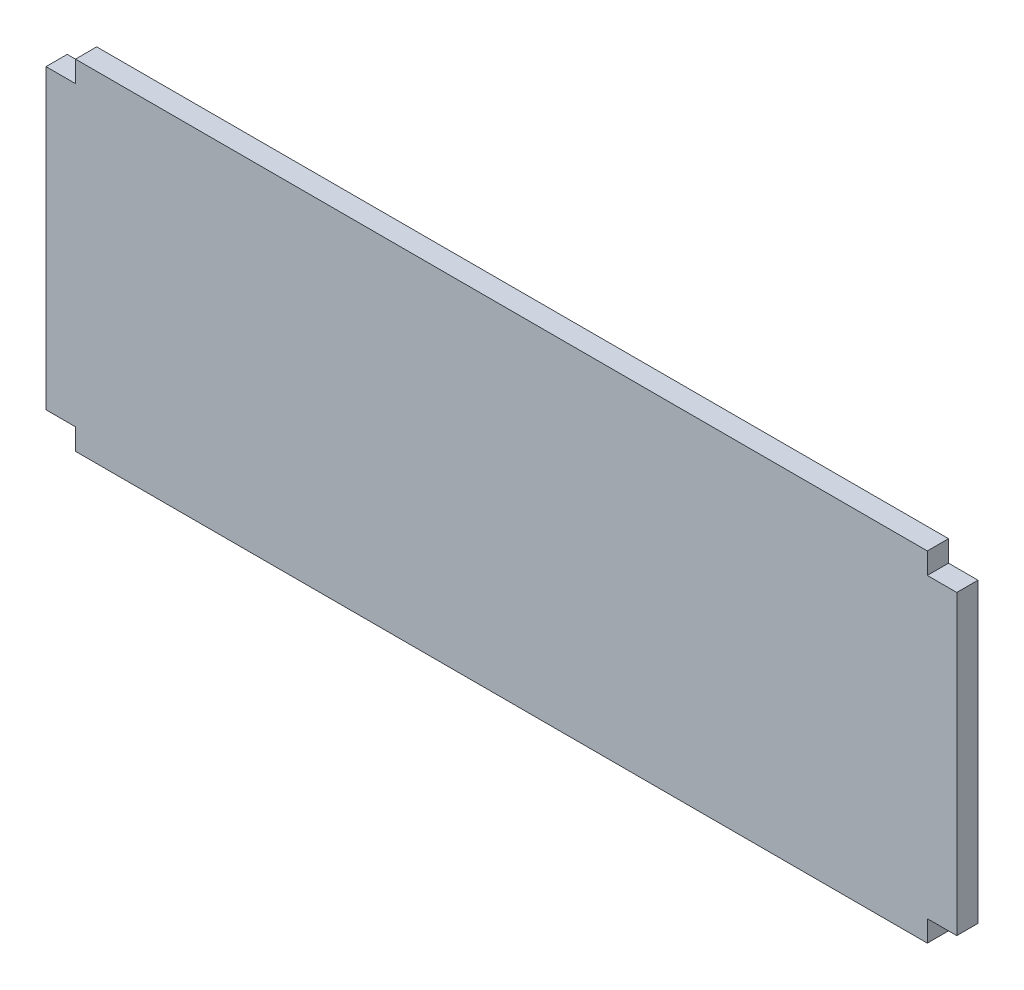
SolidWorks part; units mm, degrees
ref_plane "Front Plane" through (0, 0, 0) normal (0, 0, 1) x (1, 0, 0)
ref_plane "Top Plane" through (0, 0, 0) normal (0, 1, 0) x (1, 0, 0)
ref_plane "Right Plane" through (0, 0, 0) normal (1, 0, 0) x (0, 0, -1)
sketch "Sketch1" plane through (0, 0, 0) normal (0, 0, 1) x (1, 0, 0)
  line L0 (49.4442, 115.9117) -> (42.3963, 115.9117)
  line L1 (42.3963, 115.9117) -> (42.3963, 44.7917)
  line L2 (49.4442, 44.7917) -> (42.3963, 44.7917)
  line L3 (49.4442, 44.7917) -> (49.4442, 39.7117)
  line L4 (49.4442, 39.7117) -> (253.279, 39.7117)
  line L7 (49.4442, 120.9917) -> (49.4442, 115.9117)
  line L8 (49.4442, 120.9917) -> (253.279, 120.9917)
  line L10 (253.279, 44.7917) -> (253.279, 39.7117)
  line L11 (253.279, 44.7917) -> (260.3269, 44.7917)
  line L12 (253.279, 120.9917) -> (253.279, 115.9117)
  line L13 (260.3269, 115.9117) -> (260.3269, 44.7917)
  line L14 (253.279, 115.9117) -> (260.3269, 115.9117)
  point P23 (151.3616, 120.9917)
extrude "Boss-Extrude1" add sketch "Sketch1" along normal blind 5.08 contours L8 L12 L14 L13 L11 L10 L4 L3 L2 L1 L0 L7
